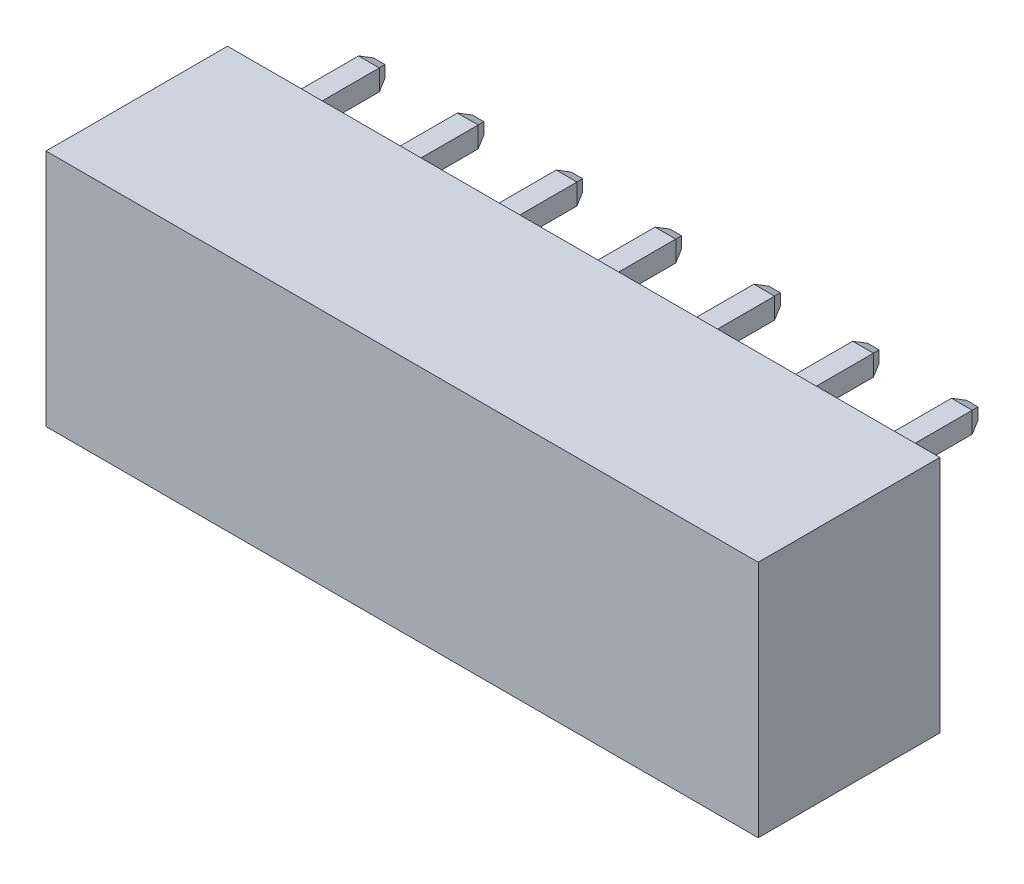
SolidWorks part; units mm, degrees
ref_plane "Спереди" through (0, 0, 0) normal (0, 0, 1) x (1, 0, 0)
ref_plane "Сверху" through (0, 0, 0) normal (0, 1, 0) x (1, 0, 0)
ref_plane "Справа" through (0, 0, 0) normal (1, 0, 0) x (0, 0, -1)
sketch "Эскиз1" plane through (0, 0, 0) normal (0, 0, 1) x (1, 0, 0)
  line L1 (13.73, 9.2) -> (-13.73, 9.2)
  line L2 (13.73, 9.2) -> (13.73, 0)
  line L3 (13.73, 0) -> (-13.73, 0)
  line L4 (-13.73, 9.2) -> (-13.73, 0)
  line L5 (13.73, 9.2) -> (-13.73, 0) construction
  line L6 (13.73, 0) -> (-13.73, 9.2) construction
  point P0 (0, 4.6)
  dimension "D1" = 9.2
  dimension "D2" = 27.46
extrude "Бобышка-Вытянуть1" add sketch "Эскиз1" along normal blind 7
sketch "Эскиз2" plane through (0, 0, 0) normal (0, 0, -1) x (-1, 0, 0)
  line L0 (13.73, 0) -> (-13.73, 0) construction
  line L1 (-11.98, 7.6) -> (-11.18, 7.6)
  line L2 (-11.98, 7.6) -> (-11.98, 8.4)
  line L3 (-11.98, 8.4) -> (-11.18, 8.4)
  line L4 (-11.18, 7.6) -> (-11.18, 8.4)
  line L5 (-11.98, 7.6) -> (-11.18, 8.4) construction
  line L6 (-11.98, 8.4) -> (-11.18, 7.6) construction
  line L7 (-13.73, 0) -> (-13.73, 9.2) construction
  point P0 (-11.58, 8)
  dimension "D1" = 8
  dimension "D2" = 0.8
  dimension "D3" = 2.15
extrude "Бобышка-Вытянуть2" add sketch "Эскиз2" along normal blind 3.4
chamfer "Фаска1" distance 0.4 angle 24 4 edges at (11.58, 8.4, -3.4) (11.18, 8, -3.4) (11.58, 7.6, -3.4) (11.98, 8, -3.4)
sketch "Эскиз3" plane through (0, 0, 0) normal (0, -1, 0) x (1, 0, 0)
  line L1 (9.98, 0.8) -> (13.08, 0.8)
  line L2 (9.98, 0.8) -> (9.98, 5)
  line L4 (13.08, 0.8) -> (13.08, 5)
  line L5 (9.98, 0.8) -> (13.08, 5) construction
  line L6 (9.98, 5) -> (13.08, 0.8) construction
  line L7 (-13.73, 0) -> (13.73, 0) construction
  line L9 (13.73, 7) -> (13.73, 0) construction
  line L10 (-13.73, 7) -> (13.73, 7) construction
  line L11 (9.98, 6.5) -> (13.08, 6.5)
  line L12 (9.98, 5) -> (10.98, 5)
  line L13 (10.98, 5) -> (9.98, 6.5)
  line L14 (13.08, 5) -> (12.08, 5)
  line L15 (12.08, 5) -> (13.08, 6.5)
  point P0 (11.53, 2.9)
  point P5 (11.53, 6.5)
  dimension "D1" = 2.2
  dimension "D2" = 0.8
  dimension "D3" = 2
  dimension "D4" = 3.1
  dimension "D5" = 0.5
  dimension "D6" = 1
extrude "Вырез-Вытянуть1" cut sketch "Эскиз3" against normal blind 7
pattern_linear "Линейный массив1" count 7 spacing 3.81 along (-1, 0, 0) of "Бобышка-Вытянуть2", "Фаска1"
pattern_linear "Линейный массив2" count 7 spacing 3.81 along (-1, 0, 0) of "Вырез-Вытянуть1"
sketch "Эскиз4" plane through (0, 7, 0) normal (0, -1, 0) x (1, 0, 0)
  line L0 (11.98, -3) -> (11.98, 0) construction
  line L1 (11.18, 3.4) -> (11.98, 3.4)
  line L2 (11.18, 3.4) -> (11.18, 2.6)
  line L3 (11.18, 2.6) -> (11.98, 2.6)
  line L4 (11.98, 3.4) -> (11.98, 2.6)
  line L5 (11.18, 3.4) -> (11.98, 2.6) construction
  line L6 (11.18, 2.6) -> (11.98, 3.4) construction
  line L7 (11.18, -3) -> (11.18, 0) construction
  line L8 (-13.73, 0) -> (13.73, 0) construction
  point P0 (11.58, 3)
  dimension "D1" = 3
extrude "Бобышка-Вытянуть3" add sketch "Эскиз4" along normal blind 6
chamfer "Фаска2" distance 0.4 angle 24 4 edges at (11.98, 1, 3) (11.58, 1, 3.4) (11.18, 1, 3) (11.58, 1, 2.6)
pattern_linear "Линейный массив3" count 7 spacing 3.81 along (-1, 0, 0) of "Фаска2", "Бобышка-Вытянуть3"
equation "\"n\"= 7"
equation "\"width\"= 3.5 * ( \"n\" - 1 ) + 4.3"
equation "\"D2@Эскиз1\"=3.81 * ( \"n\" - 1 ) + 4.6"
equation "\"D1@Линейный массив1\"=\"n\""
equation "\"D1@Линейный массив2\"=\"n\""
equation "\"D1@Линейный массив3\"=\"n\""
